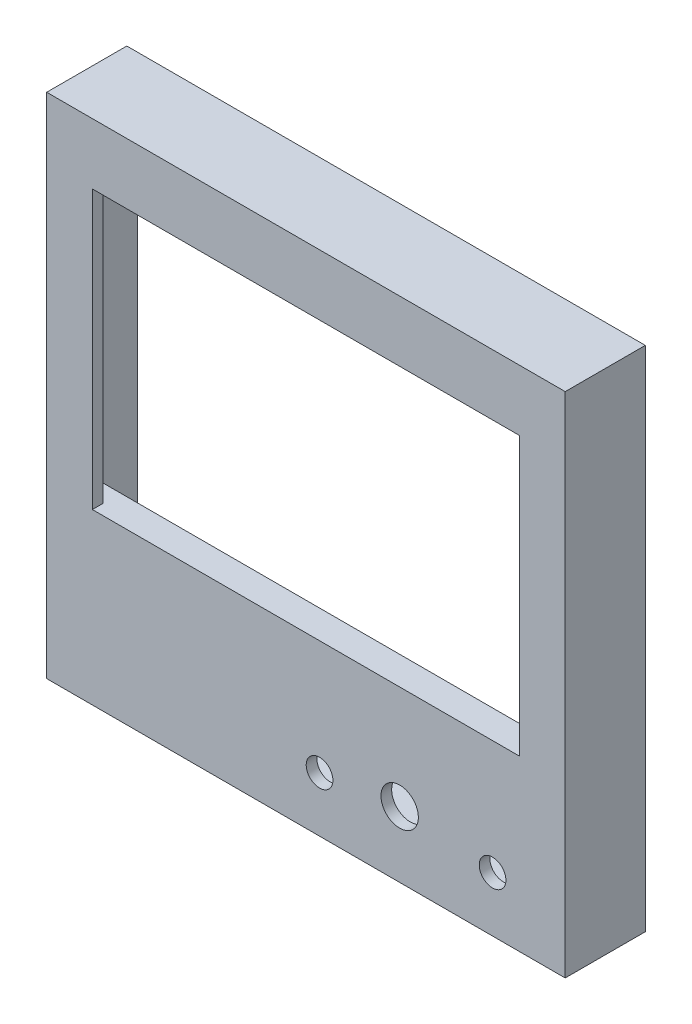
SolidWorks part; units mm, degrees
ref_plane "Front Plane" through (0, 0, 0) normal (0, 0, 1) x (1, 0, 0)
ref_plane "Top Plane" through (0, 0, 0) normal (0, 1, 0) x (1, 0, 0)
ref_plane "Right Plane" through (0, 0, 0) normal (1, 0, 0) x (0, 0, -1)
sketch "Sketch1" plane through (0, 0, 0) normal (0, 0, 1) x (1, 0, 0)
  line L0 (-46.55, -35.4) -> (-46.55, -55.7)
  line L1 (-40, -26) -> (40, -26)
  line L2 (-40, -26) -> (-40, 26)
  line L3 (-40, 26) -> (40, 26)
  line L4 (40, -26) -> (40, 26)
  line L5 (-40, -26) -> (40, 26) construction
  line L6 (-40, 26) -> (40, -26) construction
  line L7 (-46.55, -55.7) -> (46.55, -55.7)
  line L8 (-46.55, -35.4) -> (-46.55, 35.4)
  line L9 (-46.55, 35.4) -> (46.55, 35.4)
  line L10 (46.55, -35.4) -> (46.55, 35.4)
  line L11 (-46.55, -35.4) -> (46.55, 35.4) construction
  line L12 (-46.55, 35.4) -> (46.55, -35.4) construction
  line L13 (46.55, -55.7) -> (46.55, -35.4)
  point P0 (0, 0)
  point P6 (0, 0)
  dimension "D1" = 80
  dimension "D2" = 52
  dimension "D3" = 93.1
  dimension "D4" = 9.4
  dimension "D5" = 29.7
extrude "Boss-Extrude1" add sketch "Sketch1" along normal blind 2
sketch "Sketch2" plane through (0, 0, 0) normal (0, 0, -1) x (-1, 0, 0)
  line L0 (-46.55, -55.7) -> (-46.55, 35.4) construction
  line L1 (-46.55, -26) -> (46.55, -26)
  line L2 (-46.55, -26) -> (-46.55, -35.8)
  line L3 (-46.55, -35.8) -> (46.55, -35.8)
  line L4 (46.55, -26) -> (46.55, -35.8)
  line L5 (46.55, 35.4) -> (46.55, -55.7) construction
  line L6 (40, -26) -> (-40, -26) construction
  dimension "D1" = 9.8
extrude "Boss-Extrude2" add sketch "Sketch2" along normal blind 3.3
sketch "Sketch3" plane through (0, 0, 0) normal (0, 0, -1) x (-1, 0, 0)
  line L1 (-46.55, 35.4) -> (46.55, 35.4)
  line L2 (-46.55, 35.4) -> (-46.55, -55.7)
  line L3 (-46.55, -55.7) -> (46.55, -55.7)
  line L4 (46.55, 35.4) -> (46.55, -55.7)
  line L5 (-48.55, 37.4) -> (48.55, 37.4)
  line L6 (-48.55, 37.4) -> (-48.55, -57.7)
  line L7 (-48.55, -57.7) -> (48.55, -57.7)
  line L8 (48.55, 37.4) -> (48.55, -57.7)
  dimension "D1" = 2
  dimension "D2" = 2
  dimension "D3" = 2
  dimension "D4" = 2
extrude "Boss-Extrude3" add sketch "Sketch3" against normal blind 2 and the other way blind 13
sketch "Sketch4" plane through (0, 0, 2) normal (0, 0, 1) x (1, 0, 0)
  line L0 (46.55, 35.4) -> (46.55, -55.7) construction
  line L1 (48.55, -57.7) -> (-48.55, -57.7) construction
  circle A0 centre (17.55, -45.4) radius 3.5
  dimension "D2" = 7
  dimension "D1" = 29
  dimension "D3" = 12.3
extrude "Cut-Extrude1" cut sketch "Sketch4" against normal blind 29
sketch "Sketch5" plane through (0, 0, 2) normal (0, 0, 1) x (1, 0, 0)
  line L0 (48.55, 37.4) -> (48.55, -57.7) construction
  line L1 (48.55, -57.7) -> (-48.55, -57.7) construction
  circle A0 centre (2.55, -47.4) radius 2.5
  circle A1 centre (34.95, -47.4) radius 2.5
  point P8 (4.55, -50.4)
  point P9 (2.55, -48.4)
  point P10 (2.55, -47.4)
  dimension "D1" = 5
  dimension "D2" = 5
  dimension "D3" = 46
  dimension "D4" = 13.6
  dimension "D5" = 10.3
extrude "Cut-Extrude2" cut sketch "Sketch5" against normal blind 29
